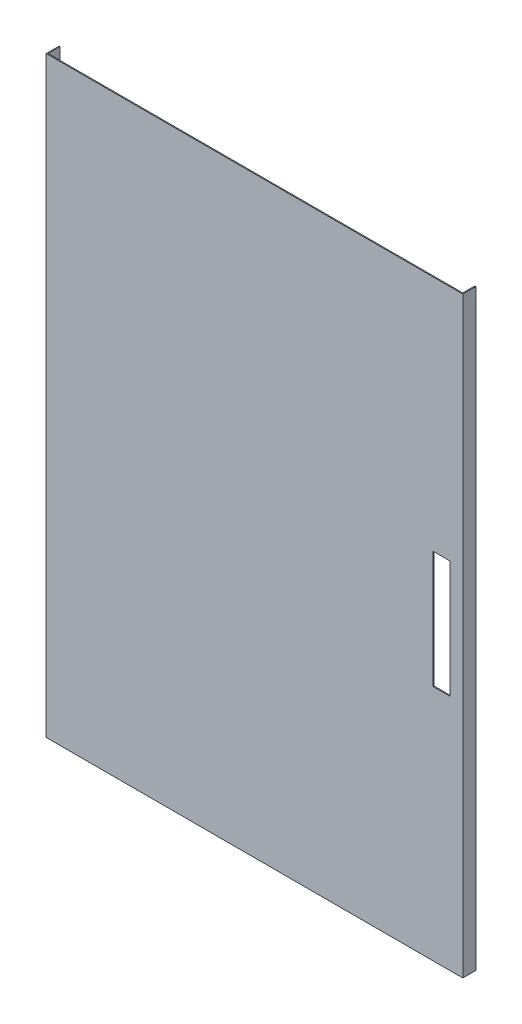
SolidWorks part; units mm, degrees
ref_plane "Front Plane" through (0, 0, 0) normal (0, 0, 1) x (1, 0, 0)
ref_plane "Top Plane" through (0, 0, 0) normal (0, 1, 0) x (1, 0, 0)
ref_plane "Right Plane" through (0, 0, 0) normal (1, 0, 0) x (0, 0, -1)
other "Configuration Table"
sketch "Sketch1" plane through (0, 0, 0) normal (0, 1, 0) x (1, 0, 0)
  line L0 (30, -40) -> (30, -20)
  line L1 (30, -20) -> (31.5, -20)
  line L2 (31.5, -20) -> (31.5, -38.5)
  line L3 (31.5, -38.5) -> (668.5, -38.5)
  line L4 (668.5, -38.5) -> (668.5, -20)
  line L5 (668.5, -20) -> (670, -20)
  line L6 (670, -20) -> (670, -40)
  line L7 (670, -40) -> (30, -40)
extrude "PACK_sarjor_kapisi_kapak_1" add sketch "Sketch1" along normal blind 910 from offset 1040 separate body
sketch "Sketch2" plane through (0, 0, 0) normal (0, 0, 1) x (1, 0, 0)
  line L1 (624, 1405) -> (650, 1405)
  line L2 (624, 1405) -> (624, 1585)
  line L3 (624, 1585) -> (650, 1585)
  line L4 (650, 1405) -> (650, 1585)
extrude "PACK_sarjor_kapisi_kapak_2" cut sketch "Sketch2" along normal blind 14 from offset 27
